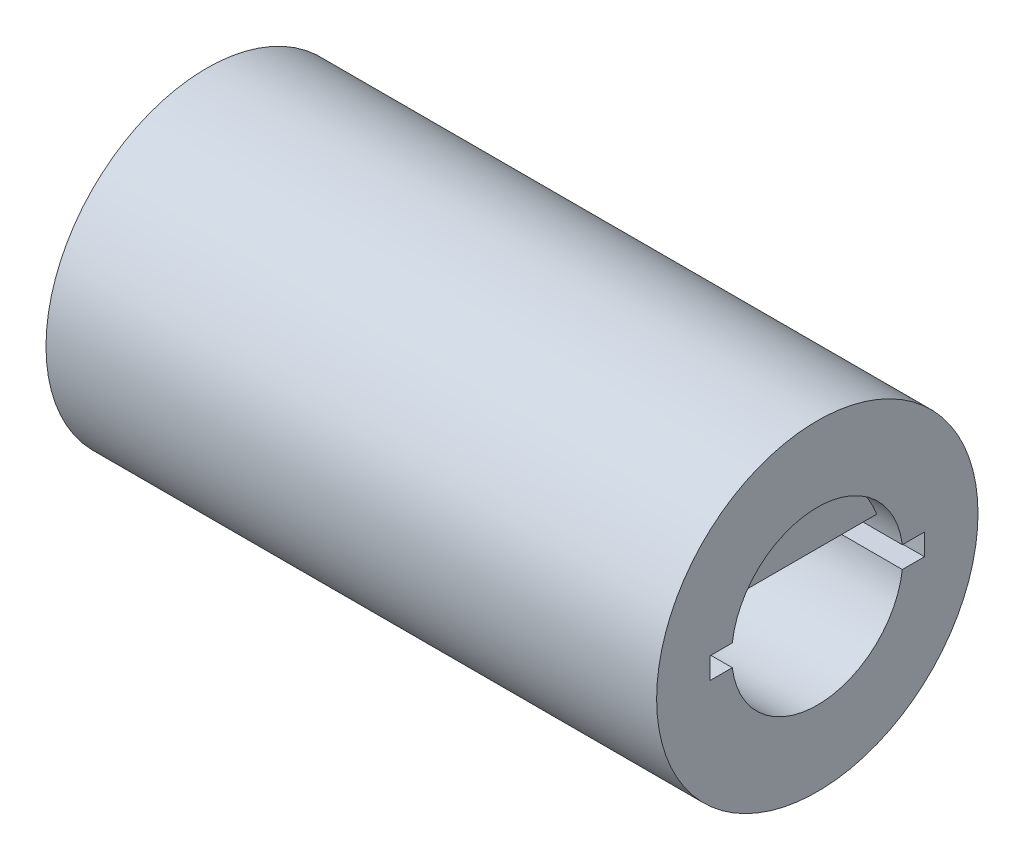
SolidWorks part; units mm, degrees
ref_plane "Front Plane" through (0, 0, 0) normal (0, 0, 1) x (1, 0, 0)
ref_plane "Top Plane" through (0, 0, 0) normal (0, 1, 0) x (1, 0, 0)
ref_plane "Right Plane" through (0, 0, 0) normal (1, 0, 0) x (0, 0, -1)
sketch "Sketch1" plane through (0, 0, 0) normal (1, 0, 0) x (0, 0, -1)
  circle A0 centre (0, 0) radius 7.5
  circle A1 centre (0, 0) radius 4
  dimension "D1" = 15
  dimension "D2" = 8
extrude "Boss-Extrude1" add sketch "Sketch1" along normal blind 8
sketch "Sketch2" plane through (0, 0, 0) normal (-1, 0, 0) x (0, 0, 1)
  circle A0 centre (0, 0) radius 7.5 construction
  circle A1 centre (0, 0) radius 7.5
extrude "Boss-Extrude2" add sketch "Sketch2" along normal blind 1
sketch "Sketch3" plane through (0, 0, 0) normal (1, 0, 0) x (0, 0, -1)
  line L0 (0, 4) -> (0, 1.3333) construction
  line L1 (0, 1.3333) -> (0, -1.3333) construction
  line L2 (0, -1.3333) -> (0, -4) construction
  line L3 (-3.7712, 1.3333) -> (3.7712, 1.3333)
  circle A0 centre (0, 0) radius 4 construction
  arc A1 (3.7712, 1.3333) -> (-3.7712, 1.3333) centre (0, 0) ccw
  arc A2 (-3.7712, 1.3333) -> (0, -4) centre (0, 0) ccw construction
  arc A3 (0, -4) -> (3.7712, 1.3333) centre (0, 0) ccw construction
extrude "Boss-Extrude3" add sketch "Sketch3" along normal blind 7
sketch "Sketch4" plane through (-1, 0, 0) normal (-1, 0, 0) x (0, 0, 1)
  line L0 (-1.5, -2) -> (1.5, -2)
  line L1 (0, 2.5) -> (0, 0) construction
  circle A0 centre (0, 0) radius 7.5 construction
  circle A1 centre (0, 0) radius 7.5
  arc A2 (1.5, -2) -> (-1.5, -2) centre (0, 0) ccw
  arc A3 (-1.5, -2) -> (1.5, -2) centre (0, 0) ccw construction
  point P6 (0, 2.5)
  circle M1 centre (0, 0) radius 7.5
  dimension "D1" = 5
  dimension "D2" = 4.5
extrude "Boss-Extrude4" add sketch "Sketch4" along normal blind 17.5 contours A2 L0 M1
sketch "Sketch5" plane through (-18.5, 0, 0) normal (-1, 0, 0) x (0, 0, 1)
  circle A0 centre (0, 0) radius 7.5 construction
  circle A1 centre (0, 0) radius 7.5
  circle A2 centre (0, 0) radius 2.5
extrude "Boss-Extrude5" add sketch "Sketch5" along normal blind 2
sketch "Sketch6" plane through (-20.5, 0, 0) normal (-1, 0, 0) x (0, 0, 1)
  line L0 (0, 0) -> (2.5, 0) construction
  line L1 (-3.5, -0.5) -> (3.5, -0.5)
  line L2 (-3.5, -0.5) -> (-3.5, 0.5)
  line L3 (-3.5, 0.5) -> (3.5, 0.5)
  line L4 (3.5, -0.5) -> (3.5, 0.5)
  line L5 (-3.5, -0.5) -> (3.5, 0.5) construction
  line L6 (-3.5, 0.5) -> (3.5, -0.5) construction
  circle A0 centre (0, 0) radius 2.5 construction
  arc A1 (1.5, -2) -> (-1.5, -2) centre (0, 0) ccw construction
  point P0 (0, 0)
  point P6 (2.5, 0)
  dimension "D1" = 1
  dimension "D2" = 1
extrude "Cut-Extrude1" cut sketch "Sketch6" against normal up to surface (19.5 mm away) up to face at (-1, 0.25, 0)
fillet "Fillet1" radius 0.2 8 edges at (-10.75, 0.5, -2.4495) (-10.75, 0.5, 2.4495) (-10.75, -0.5, 2.4495) (-10.75, -0.5, -2.4495) (-10.75, 0.5, 3.5) (-10.75, -0.5, 3.5) (-10.75, -0.5, -3.5) (-10.75, 0.5, -3.5)
sketch "Sketch7" plane through (8, 0, 0) normal (1, 0, 0) x (0, 0, -1)
  line L0 (0, 0) -> (4, 0) construction
  line L1 (-5, -0.5) -> (5, -0.5)
  line L2 (-5, -0.5) -> (-5, 0.5)
  line L3 (-5, 0.5) -> (5, 0.5)
  line L4 (5, -0.5) -> (5, 0.5)
  line L5 (-5, -0.5) -> (5, 0.5) construction
  line L6 (-5, 0.5) -> (5, -0.5) construction
  arc A0 (-3.7712, 1.3333) -> (3.7712, 1.3333) centre (0, 0) ccw construction
  point P0 (0, 0)
  dimension "D1" = 1
  dimension "D2" = 1
extrude "Cut-Extrude2" cut sketch "Sketch7" against normal up to surface (8 mm away) up to face at (0, -1.3333, 0)
